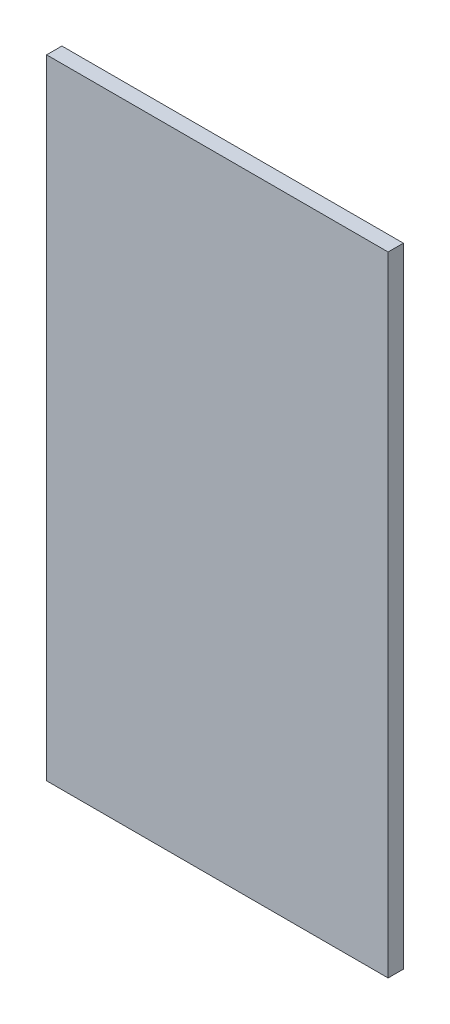
SolidWorks part; units mm, degrees
material "Cedro"
ref_plane "Piano frontale" through (0, 0, 0) normal (0, 0, 1) x (1, 0, 0)
ref_plane "Piano superiore" through (0, 0, 0) normal (0, 1, 0) x (1, 0, 0)
ref_plane "Piano destro" through (0, 0, 0) normal (1, 0, 0) x (0, 0, -1)
sketch "Schizzo1" plane through (0, 0, 0) normal (0, 0, 1) x (1, 0, 0)
  line L1 (0, 0) -> (447, 0)
  line L2 (0, 0) -> (0, 823)
  line L3 (0, 823) -> (447, 823)
  line L4 (447, 0) -> (447, 823)
  dimension "D1" = 823
  dimension "D2" = 447
extrude "Estrusione-Estrusione1" add sketch "Schizzo1" against normal blind 20
